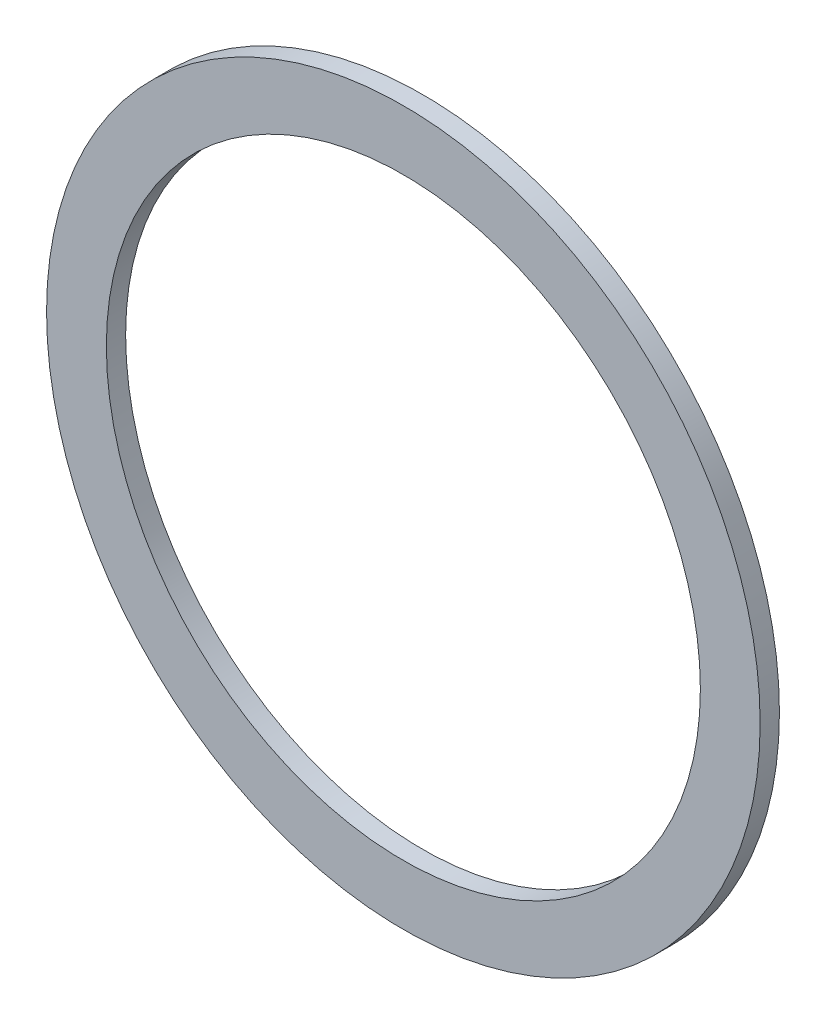
SolidWorks part; units mm, degrees
ref_plane "Спереди" through (0, 0, 0) normal (0, 0, 1) x (1, 0, 0)
ref_plane "Сверху" through (0, 0, 0) normal (0, 1, 0) x (1, 0, 0)
ref_plane "Справа" through (0, 0, 0) normal (1, 0, 0) x (0, 0, -1)
sketch "Эскиз1" plane through (0, 0, 0) normal (0, 0, 1) x (1, 0, 0)
  circle A0 centre (0, 0) radius 18.5
  circle A1 centre (0, 0) radius 15.4
extrude "Circlip_envelope" add sketch "Эскиз1" along normal blind 1 from offset 16.5
